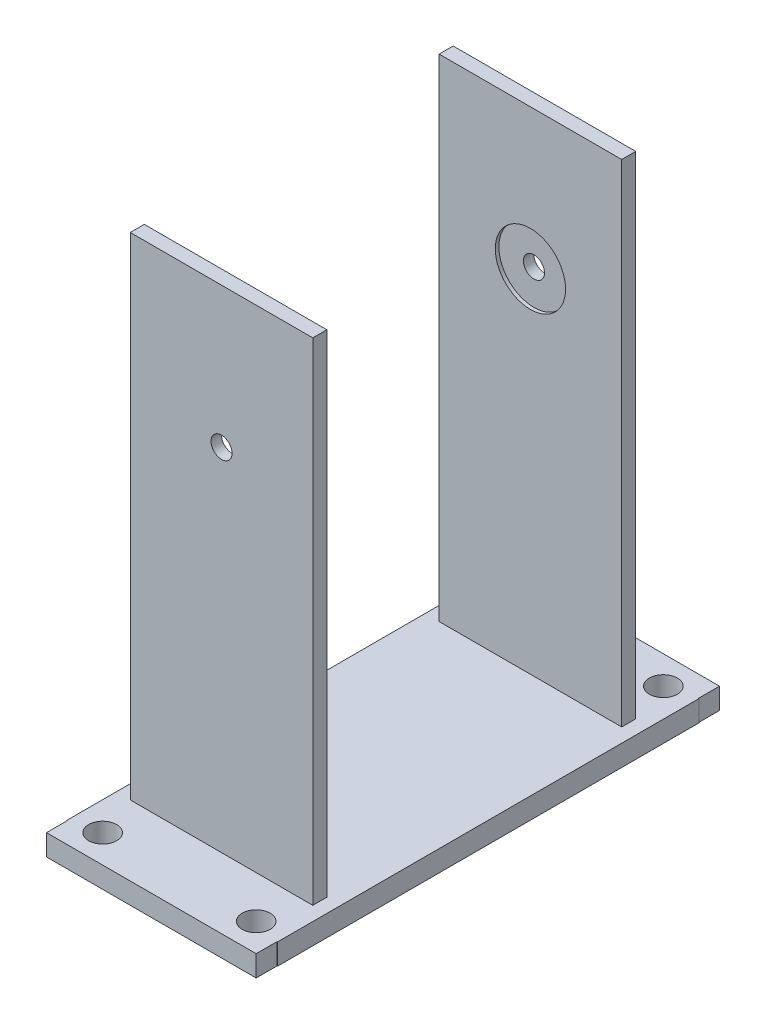
SolidWorks part; units mm, degrees
ref_plane "前视基准面" through (0, 0, 0) normal (0, 0, 1) x (1, 0, 0)
ref_plane "上视基准面" through (0, 0, 0) normal (0, 1, 0) x (1, 0, 0)
ref_plane "右视基准面" through (0, 0, 0) normal (1, 0, 0) x (0, 0, -1)
other "Configuration Table"
sketch "草图1" plane through (0, 0, 0) normal (0, 1, 0) x (1, 0, 0)
  line L1 (-15, -30) -> (15, -30)
  line L2 (-15, -30) -> (-15, 30)
  line L3 (-15, 30) -> (15, 30)
  line L4 (15, -30) -> (15, 30)
  line L5 (-15, -30) -> (15, 30) construction
  line L6 (-15, 30) -> (15, -30) construction
  point P0 (0, 0)
  dimension "D1" = 30
  dimension "D2" = 60
extrude "凸台-拉伸1" add sketch "草图1" along normal blind 3
sketch "草图2" plane through (0, 3, 0) normal (0, 1, 0) x (1, 0, 0)
  line L0 (-1000, 0) -> (49000, 0) construction
  line L1 (0, -1000) -> (0, 49000) construction
  line L2 (0, 0) -> (0, 22)
  line L3 (-13, -21) -> (13, -23) construction
  line L4 (-13, 23) -> (13, 23)
  line L5 (-13, 23) -> (-13, 21)
  line L6 (-13, 21) -> (13, 21)
  line L7 (13, 23) -> (13, 21)
  line L8 (-13, 23) -> (13, 21) construction
  line L9 (-13, 21) -> (13, 23) construction
  line L10 (-13, -23) -> (13, -21) construction
  line L11 (13, -23) -> (13, -21)
  line L12 (-13, -21) -> (13, -21)
  line L13 (-13, -23) -> (-13, -21)
  line L14 (-13, -23) -> (13, -23)
  dimension "D1" = 22
  dimension "D2" = 2
  dimension "D3" = 26
extrude "凸台-拉伸3" add sketch "草图2" along normal blind 70
sketch "草图4" plane through (0, 0, 0) normal (0, 0, 1) x (1, 0, 0)
  line L0 (0, 3) -> (0, 53)
  line L2 (-15, 3) -> (15, 3) construction
  circle A0 centre (0, 53) radius 5
  dimension "D2" = 10
  dimension "D1" = 50
extrude "切除-拉伸2" cut sketch "草图4" against normal mid plane 43
sketch "草图5" plane through (0, 0, -21.5) normal (0, 0, 1) x (1, 0, 0)
  circle A0 centre (0, 53) radius 1.5
  dimension "D1" = 3
extrude "切除-拉伸3" cut sketch "草图5" against normal through all both and the other way through all
sketch "草图7" plane through (0, 0, 0) normal (0, -1, 0) x (1, 0, 0)
  line L0 (-1000, 0) -> (49000, 0) construction
  line L1 (-15, 30) -> (-12, 30)
  line L2 (-15, 30) -> (-15, 27)
  line L3 (-15, 27) -> (-12, 27)
  line L4 (-12, 30) -> (-12, 27)
  line L5 (0, -1000) -> (0, 49000) construction
  line L8 (-14.9298, -33) -> (14.9298, -33)
  line L9 (-14.9298, -33) -> (-14.9298, 33)
  line L10 (-14.9298, 33) -> (14.9298, 33)
  line L11 (14.9298, -33) -> (14.9298, 33)
  line L12 (-14.9298, -33) -> (14.9298, 33) construction
  line L13 (-14.9298, 33) -> (14.9298, -33) construction
  circle A0 centre (-12, 27) radius 2
  circle A1 centre (12, 27) radius 2
  circle A2 centre (12, -27) radius 2
  circle A3 centre (-12, -27) radius 2
  point P18 (0, 0)
  line M6 (15, 30) -> (-15, 30)
  line M8 (-15, -30) -> (15, -30)
  dimension "D3" = 4
  dimension "D4" = 66
  dimension "D1" = 3
  dimension "D2" = 3
extrude "凸台-拉伸4" add sketch "草图7" against normal blind 3 contours L11 L10 L9 M6 | L8 L11 L9 M8
sketch "草图8" plane through (0, 0, 0) normal (0, -1, 0) x (1, 0, 0)
  line L0 (-999.5711, 0) -> (49000.4289, 0) construction
  line L1 (-14.9298, 33) -> (-10.9298, 33)
  line L2 (-14.9298, 33) -> (-14.9298, 29)
  line L3 (-14.9298, 29) -> (-10.9298, 29)
  line L4 (-10.9298, 33) -> (-10.9298, 29)
  line L6 (0, -999.1032) -> (0, 49000.8968) construction
  circle A0 centre (-10.9298, 29) radius 2
  circle A1 centre (10.9298, 29) radius 2
  circle A2 centre (10.9298, -29) radius 2
  circle A3 centre (-10.9298, -29) radius 2
  dimension "D3" = 4
  dimension "D1" = 4
  dimension "D2" = 4
extrude "切除-拉伸5" cut sketch "草图8" against normal through all both and the other way through all contours L3 A0 L4 | L4 A0 L3 | A1 | A3 | A2
